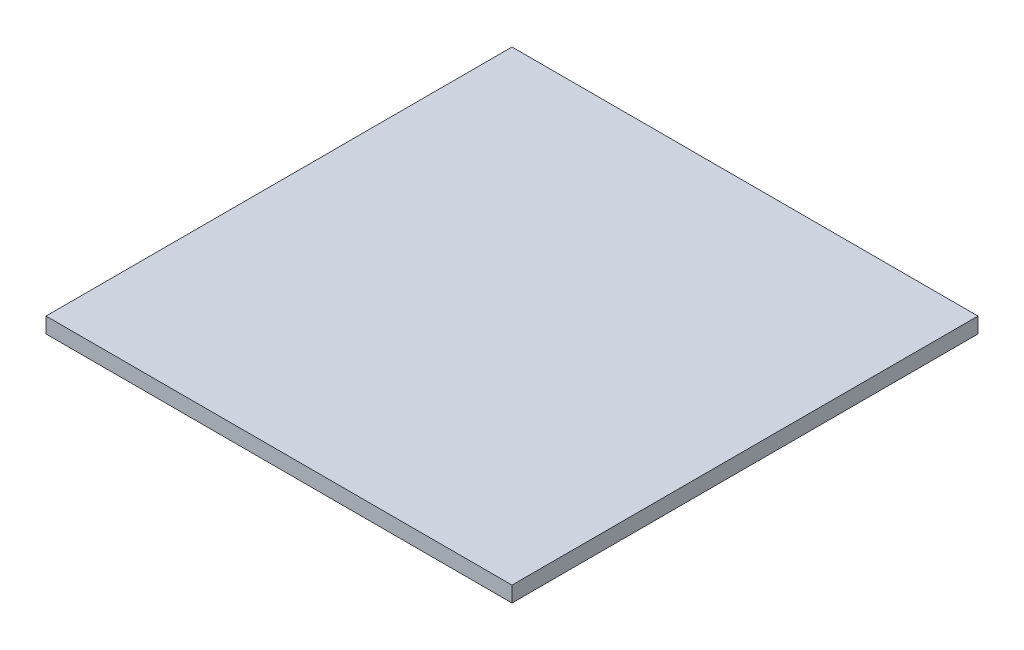
SolidWorks part; units mm, degrees
material "AISI 1020"
ref_plane "Front" through (0, 0, 0) normal (0, 0, 1) x (1, 0, 0)
ref_plane "Top" through (0, 0, 0) normal (0, 1, 0) x (1, 0, 0)
ref_plane "Right" through (0, 0, 0) normal (1, 0, 0) x (0, 0, -1)
sketch "Эскиз1" plane through (0, 0, 0) normal (0, 1, 0) x (1, 0, 0)
  line L1 (-30, -30) -> (30, -30)
  line L2 (-30, -30) -> (-30, 30)
  line L3 (-30, 30) -> (30, 30)
  line L4 (30, -30) -> (30, 30)
  line L5 (-30, -30) -> (30, 30) construction
  line L6 (-30, 30) -> (30, -30) construction
  point P0 (0, 0)
  dimension "D1" = 60
  dimension "D2" = 60
extrude "Бобышка-Вытянуть1" add sketch "Эскиз1" along normal blind 2
